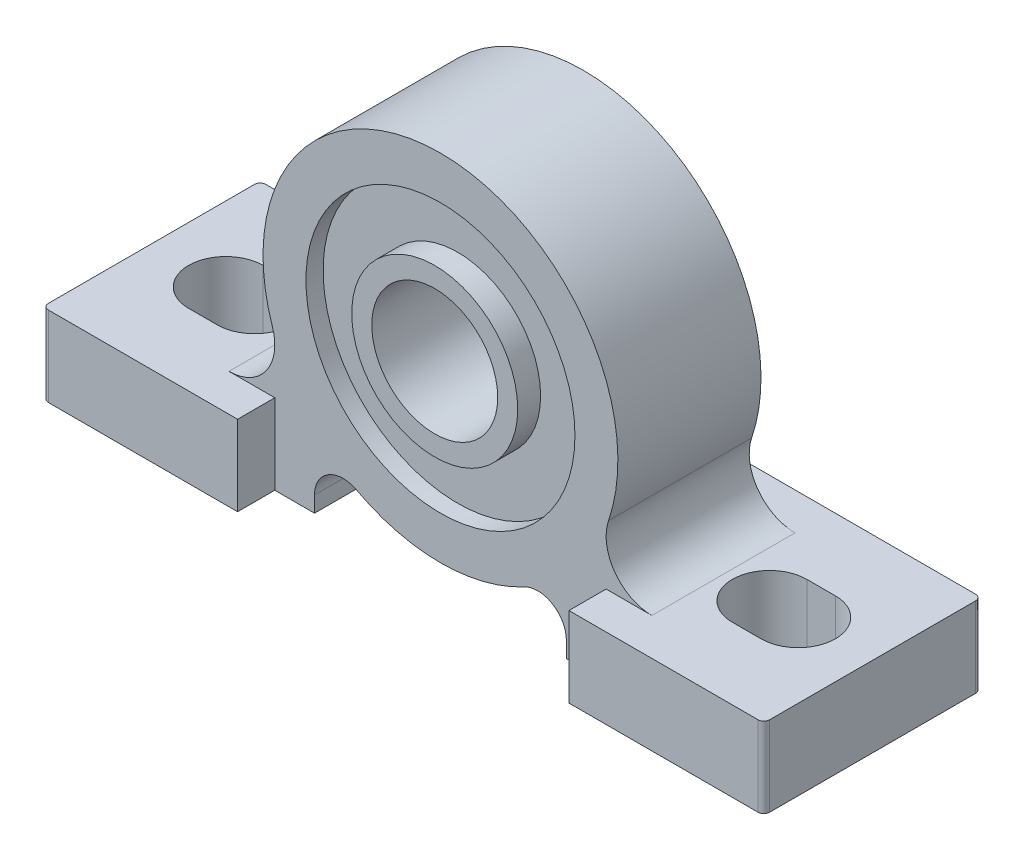
SolidWorks part; units mm, degrees
ref_plane "Спереди" through (0, 0, 0) normal (0, 0, 1) x (1, 0, 0)
ref_plane "Сверху" through (0, 0, 0) normal (0, 1, 0) x (1, 0, 0)
ref_plane "Справа" through (0, 0, 0) normal (1, 0, 0) x (0, 0, -1)
sketch "Эскиз8" plane through (0, 0, 0) normal (0, 0, 1) x (1, 0, 0)
  circle A0 centre (50, -1.5) radius 11
  circle A1 centre (50, -1.5) radius 14.5
extrude "Вытянуть1" add sketch "Эскиз8" along normal blind 31
ref_plane "Плоскость1" through (0, 0, 10) normal (0, 0, 1) x (1, 0, 0)
sketch "Эскиз10" plane through (0, 0, 10) normal (0, 0, 1) x (1, 0, 0)
  circle A0 centre (50, -1.5) radius 23.5
  circle A1 centre (50, -1.5) radius 14.5
  dimension "D1" = 29
  dimension "D2" = 47
extrude "Вытянуть2" add sketch "Эскиз10" along normal blind 17
sketch "Эскиз11" plane through (0, 0, 10) normal (0, 0, 1) x (1, 0, 0)
  circle A0 centre (50, -1.5) radius 23.5
  circle A1 centre (50, -1.5) radius 31
  dimension "D1" = 47
  dimension "D2" = 62
extrude "Вытянуть3" add sketch "Эскиз11" along normal blind 25 from offset 5 offset against normal yes
ref_plane "Плоскость2" through (0, -36, 0) normal (0, 1, 0) x (-1, 0, 0)
sketch "Эскиз13" plane through (0, -36, 0) normal (0, 1, 0) x (-1, 0, 0)
  line L1 (-95, 11) -> (-100, 11)
  line L2 (-28, 36.5) -> (13, 36.5)
  line L3 (-4.7401, 23.9948) -> (0, 24)
  line L4 (-95.2599, 23.9948) -> (-100, 24)
  line L5 (-5, 11) -> (0, 11)
  line L6 (13, -1.5) -> (13, 36.5)
  line L7 (-72, -1.5) -> (-113, -1.5)
  line L8 (-72, 36.5) -> (-113, 36.5)
  line L9 (-113, -1.5) -> (-113, 36.5)
  line L10 (-72, -1.5) -> (-72, 36.5)
  line L11 (-28, -1.5) -> (13, -1.5)
  line L12 (-28, -1.5) -> (-28, 36.5)
  arc A0 (-100, 24) -> (-100, 11) centre (-100, 17.5) ccw
  arc A1 (-95, 11) -> (-95.2599, 23.9948) centre (-95, 17.5) ccw
  arc A2 (-5, 11) -> (-4.7401, 23.9948) centre (-5, 17.5) cw
  arc A3 (0, 24) -> (0, 11) centre (0, 17.5) cw
  dimension "D1" = 6.5
  dimension "D2" = 6.5
  dimension "D3" = 6.5
  dimension "D4" = 6.5
  dimension "D5" = 41
  dimension "D6" = 38
  dimension "D7" = 44
  dimension "D8" = 41
  dimension "D9" = 38
  dimension "D10" = 18
  dimension "D11" = 13
  dimension "D12" = 41
  dimension "D13" = 38
  dimension "D14" = 38
  dimension "D15" = 41
  dimension "D16" = 13
  dimension "D17" = 113
  dimension "D18" = 4.7401
  dimension "D19" = 0.2599
  dimension "D20" = 23
  dimension "D21" = 0.2599
  dimension "D22" = 4.7401
  dimension "D23" = 17.5
  dimension "D24" = 17.5
  dimension "D25" = 23.9948
  dimension "D26" = 23.9948
  dimension "D27" = 36.5
  dimension "D28" = 36.5
extrude "Вытянуть4" add sketch "Эскиз13" along normal blind 14
ref_plane "Плоскость3" through (26.746, -22, 5) normal (0, 0, -1) x (-1, 0, 0)
fillet "Скругление1" radius 8 1 edges at (26.746, -22, 17.5)
fillet "Скругление2" radius 5 1 edges at (28, -23.3403, 17.5)
fillet "Скругление3" radius 5 1 edges at (72, -23.3403, 17.5)
fillet "Скругление4" radius 8 1 edges at (73.254, -22, 17.5)
fillet "Скругление5" radius 1 4 edges at (28, -29, 36.5) (28, -29, -1.5) (72, -29, 36.5) (72, -29, -1.5)
fillet "Скругление6" radius 1 4 edges at (-13, -29, -1.5) (-13, -29, 36.5) (113, -29, 36.5) (113, -29, -1.5)
sketch "Эскиз14" plane through (0, -22, 0) normal (0, 1, 0) x (1, 0, 0)
  line L0 (50, -30) -> (50, -51.3805) construction
  line L2 (21.0575, -30) -> (21.0575, -39.4968)
  line L3 (21.0575, -39.4968) -> (33.7473, -39.4968)
  line L4 (33.7473, -39.4968) -> (33.7473, -30)
  line L5 (19, -30) -> (81, -30) construction
  line L6 (33.7473, -30) -> (21.0575, -30)
  line L7 (78.9425, -39.4968) -> (66.2527, -39.4968)
  line L8 (66.2527, -39.4968) -> (66.2527, -30)
  line L9 (66.2527, -30) -> (78.9425, -30)
  line L10 (78.9425, -30) -> (78.9425, -39.4968)
extrude "Вытянуть5" cut sketch "Эскиз14" against normal through all
